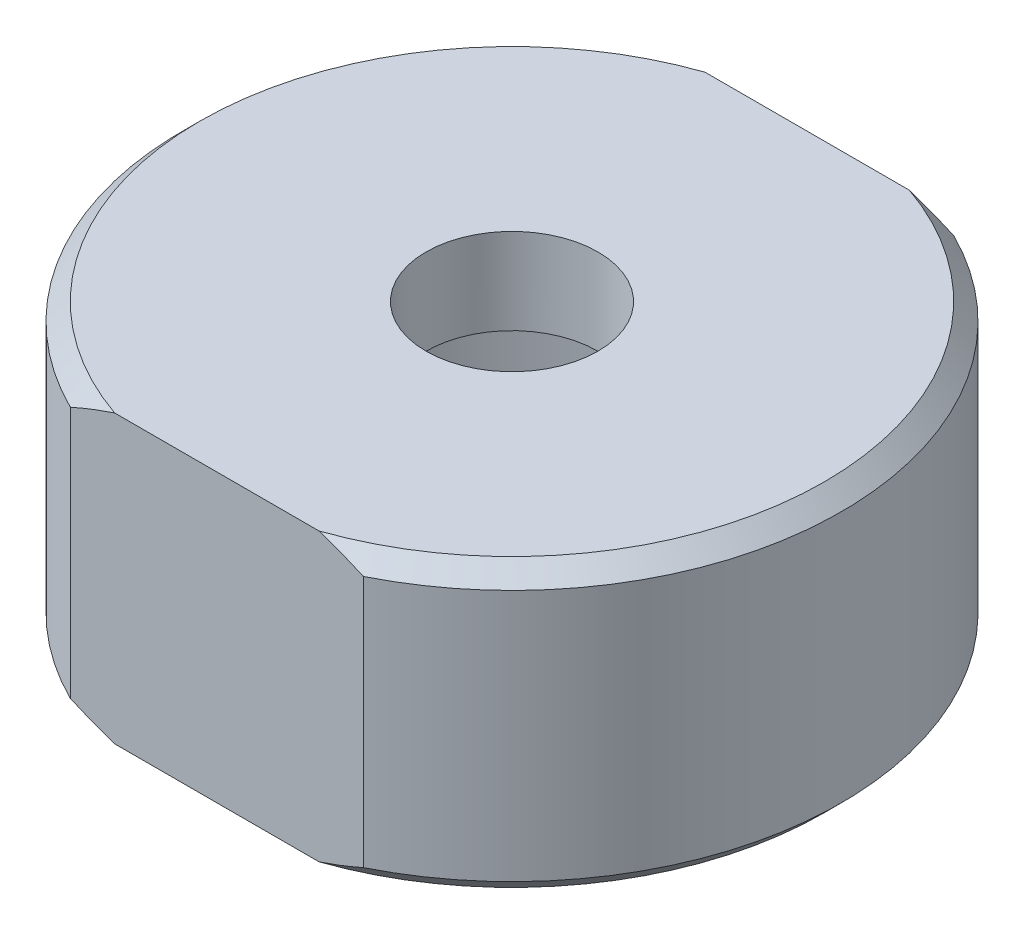
SolidWorks part; units mm, degrees
material "5052-H34"
ref_plane "正面" through (0, 0, 0) normal (0, 0, 1) x (1, 0, 0)
ref_plane "平面" through (0, 0, 0) normal (0, 1, 0) x (1, 0, 0)
ref_plane "右側面" through (0, 0, 0) normal (1, 0, 0) x (0, 0, -1)
sketch "ｽｹｯﾁ1" plane through (0, 0, 0) normal (0, 1, 0) x (1, 0, 0)
  line L0 (-2.5573, -5.15) -> (2.5573, -5.15)
  line L1 (0, 0) -> (5.75, 0) construction
  line L2 (-2.5573, 5.15) -> (2.5573, 5.15)
  arc A0 (-2.5573, 5.15) -> (-2.5573, -5.15) centre (0, 0) ccw
  arc A1 (2.5573, -5.15) -> (2.5573, 5.15) centre (0, 0) ccw
  circle A2 centre (0, 0) radius 1.5
  dimension "D1" = 11.5
  dimension "D3" = 3
  dimension "D2" = 10.3
extrude "ﾎﾞｽ - 押し出し1" add sketch "ｽｹｯﾁ1" along normal blind 5
sketch "ｽｹｯﾁ2" plane through (0, 0, 0) normal (0, -1, 0) x (1, 0, 0)
  circle A0 centre (0, 0) radius 4.9
  dimension "D1" = 9.8
extrude "ｶｯﾄ - 押し出し1" cut sketch "ｽｹｯﾁ2" against normal blind 3.5
chamfer "面取り1" distance 0.3 angle 45 4 edges at (-5.75, 0, 0) (5.75, 0, 0) (-5.75, 5, 0) (5.75, 5, 0)
